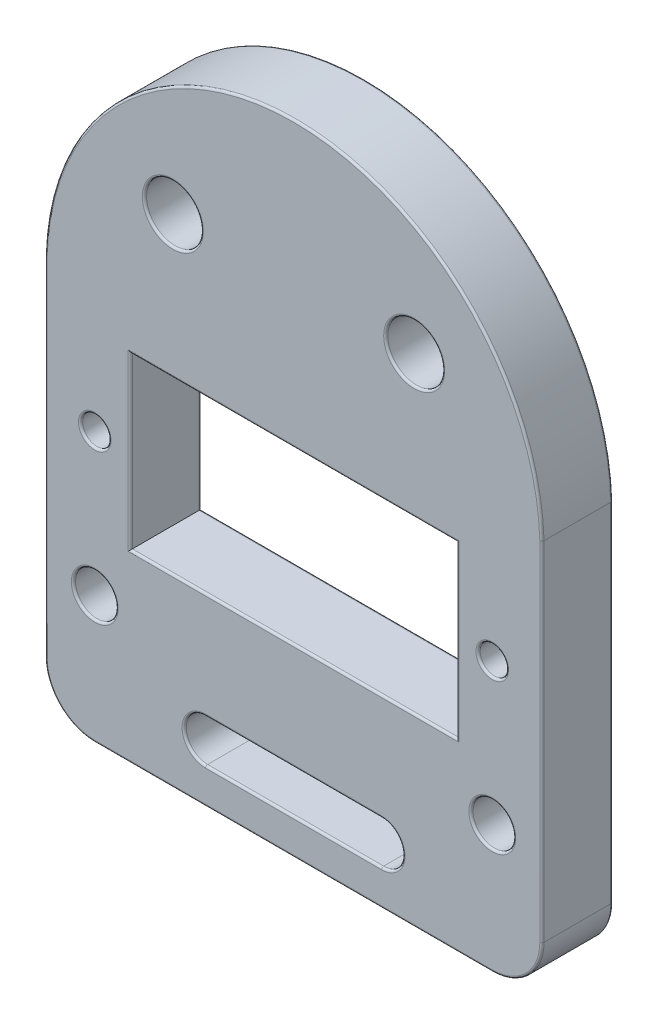
SolidWorks part; units mm, degrees
ref_plane "Front Plane" through (0, 0, 0) normal (0, 0, 1) x (1, 0, 0)
ref_plane "Top Plane" through (0, 0, 0) normal (0, 1, 0) x (1, 0, 0)
ref_plane "Right Plane" through (0, 0, 0) normal (1, 0, 0) x (0, 0, -1)
sketch "Sketch1" plane through (0, 0, 0) normal (0, 0, 1) x (1, 0, 0)
  line L0 (0, -19) -> (0, 26) construction
  line L1 (11.5, -6) -> (-11.5, -6)
  line L2 (11.5, -6) -> (11.5, 6)
  line L3 (11.5, 6) -> (-11.5, 6)
  line L4 (-11.5, -6) -> (-11.5, 6)
  line L5 (11.5, -6) -> (-11.5, 6) construction
  line L6 (11.5, 6) -> (-11.5, -6) construction
  line L7 (6.2, -15) -> (-6.2, -15) construction
  line L8 (6.2, -16.5) -> (-6.2, -16.5)
  line L9 (6.2, -13.5) -> (-6.2, -13.5)
  line L11 (-17.5, 9) -> (17.5, 9) construction
  line L12 (-17.5, 9) -> (-17.5, -19)
  line L13 (-17.5, -19) -> (17.5, -19)
  line L14 (17.5, 9) -> (17.5, -19)
  circle A0 centre (-14, 0) radius 1
  circle A1 centre (-14, -10) radius 1.5
  arc A2 (6.2, -16.5) -> (6.2, -13.5) centre (6.2, -15) ccw
  arc A3 (-6.2, -13.5) -> (-6.2, -16.5) centre (-6.2, -15) ccw
  circle A4 centre (-8.5, 16) radius 2
  circle A5 centre (14, -10) radius 1.5
  circle A6 centre (14, 0) radius 1
  circle A7 centre (8.5, 16) radius 2
  arc A8 (-17.5, 9) -> (17.5, 9) centre (0, 8.4926) cw
  point P0 (0, 0)
  point P14 (0, -15)
  point P25 (0, -19)
  dimension "D5" = 2
  dimension "D7" = 3
  dimension "D11" = 1.5
  dimension "D12" = 4
  dimension "D13" = 10
  dimension "D1" = 23
  dimension "D2" = 12
  dimension "D3" = 45
  dimension "D6" = 2.5
  dimension "D8" = 10
  dimension "D9" = 12.4
  dimension "D10" = 4
  dimension "D14" = 8.5
  dimension "D15" = 35
  dimension "D16" = 28
  dimension "D17" = 13
extrude "Boss-Extrude1" add sketch "Sketch1" along normal blind 5
fillet "Fillet1" radius 3.5 2 edges at (-17.5, -19, 2.5) (17.5, -19, 2.5)
fillet "Fillet2" radius 0.15 40 edges at (6.5, 16, 5) (12.5, -10, 5) (0, -13.5, 5) (-7.7, -15, 5) (0, -16.5, 5) (7.7, -15, 5) (-13, 0, 5) (0, 26, 5) (17.5, -3.25, 5) (16.4749, -17.9749, 5) (0, -19, 5) (-16.4749, -17.9749, 5) (-17.5, -3.25, 5) (0, -6, 5) (11.5, 0, 5) (0, 6, 5) (-11.5, 0, 5) (-12.5, -10, 5) (-6.5, 16, 5) (13, 0, 5) (6.5, 16, 0) (12.5, -10, 0) (-7.7, -15, 0) (0, -13.5, 0) (7.7, -15, 0) (0, -16.5, 0) (-13, 0, 0) (16.4749, -17.9749, 0) (17.5, -3.25, 0) (0, 26, 0) (-17.5, -3.25, 0) (-16.4749, -17.9749, 0) (0, -19, 0) (11.5, 0, 0) (0, -6, 0) (-11.5, 0, 0) (0, 6, 0) (-12.5, -10, 0) (-6.5, 16, 0) (13, 0, 0)
